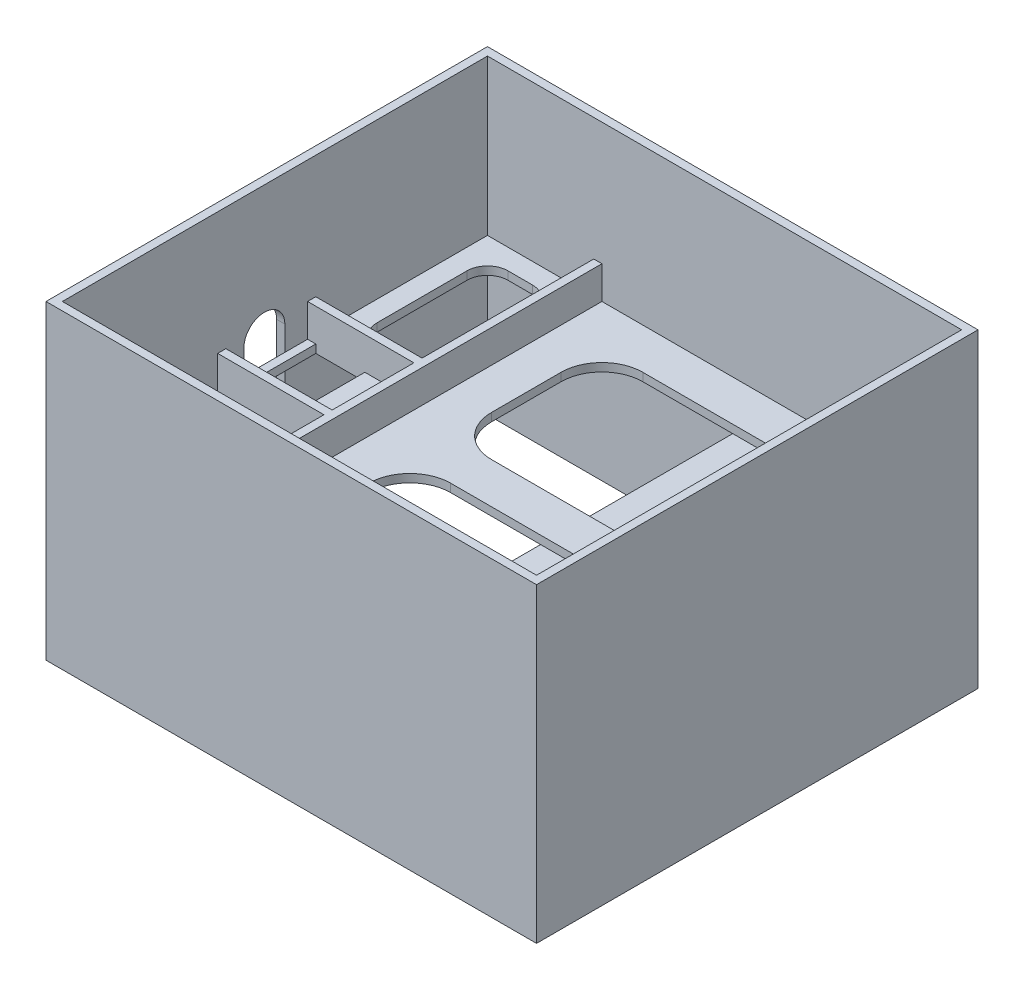
SolidWorks part; units mm, degrees
ref_plane "Front Plane" through (0, 0, 0) normal (0, 0, 1) x (1, 0, 0)
ref_plane "Top Plane" through (0, 0, 0) normal (0, 1, 0) x (1, 0, 0)
ref_plane "Right Plane" through (0, 0, 0) normal (1, 0, 0) x (0, 0, -1)
sketch "Sketch1" plane through (0, 0, 0) normal (0, 1, 0) x (1, 0, 0)
  line L1 (-113.8745, -60.9464) -> (-53.8745, -60.9464)
  line L2 (-113.8745, -60.9464) -> (-113.8745, -6.9464)
  line L3 (-113.8745, -6.9464) -> (-53.8745, -6.9464)
  line L4 (-53.8745, -60.9464) -> (-53.8745, -6.9464)
  dimension "D1" = 60
  dimension "D2" = 54
extrude "Boss-Extrude1" add sketch "Sketch1" along normal blind 38
sketch "Sketch2" plane through (0, 38, 0) normal (0, 1, 0) x (1, 0, 0)
  line L0 (-53.8745, -60.9464) -> (-53.8745, -6.9464) construction
  line L1 (-54.8745, -7.9464) -> (-98.8745, -7.9464)
  line L2 (-54.8745, -7.9464) -> (-54.8745, -59.9464)
  line L3 (-54.8745, -59.9464) -> (-98.8745, -59.9464)
  line L4 (-98.8745, -7.9464) -> (-98.8745, -59.9464)
  line L5 (-53.8745, -6.9464) -> (-113.8745, -6.9464) construction
  line L6 (-113.8745, -60.9464) -> (-53.8745, -60.9464) construction
  dimension "D1" = 1
  dimension "D2" = 1
  dimension "D3" = 1
  dimension "D4" = 44
extrude "Cut-Extrude1" cut sketch "Sketch2" against normal blind 19
sketch "Sketch3" plane through (0, 0, 0) normal (0, -1, 0) x (-1, 0, 0)
  line L0 (113.8745, -60.9464) -> (53.8745, -60.9464) construction
  line L1 (112.8745, -59.9464) -> (77.8745, -59.9464)
  line L2 (112.8745, -59.9464) -> (112.8745, -7.9464)
  line L3 (112.8745, -7.9464) -> (77.8745, -7.9464)
  line L4 (77.8745, -59.9464) -> (77.8745, -7.9464)
  line L5 (113.8745, -6.9464) -> (113.8745, -60.9464) construction
  line L6 (53.8745, -6.9464) -> (113.8745, -6.9464) construction
  dimension "D1" = 1
  dimension "D2" = 35
  dimension "D3" = 1
  dimension "D4" = 1
extrude "Cut-Extrude2" cut sketch "Sketch3" against normal blind 18
sketch "Sketch4" plane through (0, 18, 0) normal (0, -1, 0) x (-1, 0, 0)
  line L0 (77.8745, -59.9464) -> (112.8745, -59.9464) construction
  line L1 (111.8745, -39.9464) -> (105.8745, -39.9464)
  line L2 (111.8745, -39.9464) -> (111.8745, -29.9464)
  line L3 (111.8745, -29.9464) -> (105.8745, -29.9464)
  line L4 (105.8745, -39.9464) -> (105.8745, -29.9464)
  line L5 (112.8745, -7.9464) -> (77.8745, -7.9464) construction
  line L6 (112.8745, -59.9464) -> (112.8745, -7.9464) construction
  dimension "D1" = 20
  dimension "D2" = 22
  dimension "D3" = 1
  dimension "D4" = 6
extrude "Cut-Extrude3" cut sketch "Sketch4" against normal blind 38
sketch "Sketch5" plane through (0, 38, 0) normal (0, 1, 0) x (1, 0, 0)
  line L0 (-53.8745, -6.9464) -> (-113.8745, -6.9464) construction
  line L1 (-98.8745, -59.9464) -> (-112.8745, -59.9464)
  line L2 (-98.8745, -59.9464) -> (-98.8745, -7.9464)
  line L3 (-98.8745, -7.9464) -> (-112.8745, -7.9464)
  line L4 (-112.8745, -59.9464) -> (-112.8745, -7.9464)
  line L5 (-113.8745, -6.9464) -> (-113.8745, -60.9464) construction
  dimension "D1" = 1
  dimension "D2" = 1
extrude "Cut-Extrude5" cut sketch "Sketch5" against normal blind 15
sketch "Sketch6" plane through (0, 23, 0) normal (0, 1, 0) x (1, 0, 0)
  line L0 (-112.8745, -59.9464) -> (-98.8745, -59.9464) construction
  line L1 (-112.8745, -7.9464) -> (-99.8745, -7.9464)
  line L2 (-112.8745, -7.9464) -> (-112.8745, -59.9464)
  line L3 (-112.8745, -59.9464) -> (-99.8745, -59.9464)
  line L4 (-99.8745, -7.9464) -> (-99.8745, -59.9464)
  line L5 (-98.8745, -59.9464) -> (-98.8745, -7.9464) construction
  dimension "D1" = 1
extrude "Cut-Extrude6" cut sketch "Sketch6" against normal blind 4
sketch "Sketch8" plane through (0, 0, 0) normal (0, -1, 0) x (-1, 0, 0)
  line L0 (53.8745, -60.9464) -> (53.8745, -6.9464) construction
  line L1 (73.3745, -11.4464) -> (58.3745, -11.4464)
  line L2 (73.3745, -11.4464) -> (73.3745, -24.4464)
  line L3 (73.3745, -24.4464) -> (58.3745, -24.4464)
  line L4 (58.3745, -11.4464) -> (58.3745, -24.4464)
  line L6 (53.8745, -6.9464) -> (113.8745, -6.9464) construction
  dimension "D1" = 15
  dimension "D2" = 13
  dimension "D3" = 4.5
  dimension "D4" = 4.5
extrude "Cut-Extrude7" cut sketch "Sketch8" against normal blind 6
sketch "Sketch10" plane through (-73.3745, 0, 0) normal (1, 0, 0) x (0, 0, -1)
  line L0 (-11.4464, 6) -> (-11.4464, 0) construction
  line L1 (-24.4464, 6) -> (-11.4464, 6)
  line L2 (-24.4464, 6) -> (-24.4464, 1)
  line L3 (-24.4464, 1) -> (-11.4464, 1)
  line L4 (-11.4464, 6) -> (-11.4464, 1)
  line L5 (-24.4464, 0) -> (-11.4464, 0) construction
  point P7 (-11.9162, 2.727)
  dimension "D1" = 1
extrude "Cut-Extrude8" cut sketch "Sketch10" against normal blind 6
sketch "Sketch11" plane through (0, 0, 0) normal (0, -1, 0) x (1, 0, 0)
  line L0 (-113.8745, 60.9464) -> (-53.8745, 60.9464) construction
  line L1 (-67.8745, 50.9464) -> (-63.8745, 50.9464)
  line L2 (-67.8745, 50.9464) -> (-67.8745, 45.9464)
  line L3 (-67.8745, 45.9464) -> (-63.8745, 45.9464)
  line L4 (-63.8745, 50.9464) -> (-63.8745, 45.9464)
  line L5 (-53.8745, 60.9464) -> (-53.8745, 6.9464) construction
  dimension "D1" = 4
  dimension "D2" = 5
  dimension "D3" = 10
  dimension "D4" = 10
extrude "Cut-Extrude9" cut sketch "Sketch11" against normal blind 3
sketch "Sketch12" plane through (-67.8745, 0, 0) normal (1, 0, 0) x (0, 0, -1)
  line L0 (-50.9464, 3) -> (-50.9464, 0) construction
  line L1 (-45.9464, 3) -> (-50.9464, 3)
  line L2 (-45.9464, 3) -> (-45.9464, 1)
  line L3 (-45.9464, 1) -> (-50.9464, 1)
  line L4 (-50.9464, 3) -> (-50.9464, 1)
  line L5 (-50.9464, 0) -> (-45.9464, 0) construction
  point P7 (-49.533, -3.8829)
  dimension "D1" = 1
extrude "Cut-Extrude10" cut sketch "Sketch12" against normal blind 13
sketch "Sketch13" plane through (-113.8745, 0, 0) normal (-1, 0, 0) x (0, 0, 1)
  line L0 (35.233, 15) -> (35.233, 22) construction
  line L1 (32.733, 15) -> (32.733, 22)
  line L2 (37.733, 15) -> (37.733, 22)
  line L3 (59.9464, 18) -> (7.9464, 18) construction
  line L4 (39.9464, 19) -> (29.9464, 19) construction
  arc A0 (32.733, 15) -> (37.733, 15) centre (35.233, 15) ccw
  arc A1 (37.733, 22) -> (32.733, 22) centre (35.233, 22) ccw
  point P2 (35.233, 18.5)
  point P7 (0, 0)
  point P8 (14.7226, 4.5519)
  dimension "D1" = 3
  dimension "D2" = 3
  dimension "D3" = 2.5
extrude "Cut-Extrude11" cut sketch "Sketch13" against normal blind 1
sketch "Sketch14" plane through (0, 19, 0) normal (0, 1, 0) x (1, 0, 0)
  line L0 (-99.8745, -59.9464) -> (-99.8745, -7.9464) construction
  line L1 (-112.8745, -40.9464) -> (-99.8745, -40.9464)
  line L2 (-112.8745, -40.9464) -> (-112.8745, -39.9464)
  line L3 (-112.8745, -39.9464) -> (-99.8745, -39.9464)
  line L4 (-99.8745, -40.9464) -> (-99.8745, -39.9464)
  line L5 (-112.8745, -37.733) -> (-112.8745, -59.9464) construction
  line L6 (-105.8745, -39.9464) -> (-111.8745, -39.9464) construction
  point P6 (-120.1002, -35.2386)
  point P7 (-123.1182, -45.5085)
  point P8 (-107.1478, -38.8588)
  dimension "D1" = 0
  dimension "D2" = 1
  dimension "D3" = 0
extrude "Boss-Extrude2" add sketch "Sketch14" along normal blind 4
sketch "Sketch15" plane through (0, 19, 0) normal (0, 1, 0) x (1, 0, 0)
  line L0 (-112.8745, -7.9464) -> (-112.8745, -32.733) construction
  line L1 (-112.8745, -29.9464) -> (-99.8745, -29.9464)
  line L2 (-112.8745, -29.9464) -> (-112.8745, -28.9464)
  line L3 (-112.8745, -28.9464) -> (-99.8745, -28.9464)
  line L4 (-99.8745, -29.9464) -> (-99.8745, -28.9464)
  line L5 (-99.8745, -39.9464) -> (-99.8745, -7.9464) construction
  line L6 (-111.8745, -29.9464) -> (-105.8745, -29.9464) construction
  point P8 (-103.7086, -29.8744)
  dimension "D1" = 0
  dimension "D2" = 1
extrude "Boss-Extrude3" add sketch "Sketch15" along normal blind 4
sketch "Sketch16" plane through (0, 19, 0) normal (0, 1, 0) x (1, 0, 0)
  line L0 (-98.8745, -59.9464) -> (-54.8745, -59.9464) construction
  line L1 (-64.8745, -54.9464) -> (-88.8745, -54.9464)
  line L2 (-59.8745, -49.9464) -> (-59.8745, -41.4464)
  line L3 (-64.8745, -36.4464) -> (-88.8745, -36.4464)
  line L4 (-93.8745, -49.9464) -> (-93.8745, -41.4464)
  line L5 (-88.8745, -31.4464) -> (-64.8745, -31.4464)
  line L6 (-93.8745, -26.4464) -> (-93.8745, -17.9464)
  line L7 (-88.8745, -12.9464) -> (-64.8745, -12.9464)
  line L8 (-59.8745, -26.4464) -> (-59.8745, -17.9464)
  line L9 (-54.8745, -59.9464) -> (-54.8745, -7.9464) construction
  line L10 (-98.8745, -7.9464) -> (-98.8745, -59.9464) construction
  line L11 (-54.8745, -7.9464) -> (-98.8745, -7.9464) construction
  arc A0 (-64.8745, -31.4464) -> (-59.8745, -26.4464) centre (-64.8745, -26.4464) ccw
  arc A1 (-64.8745, -12.9464) -> (-59.8745, -17.9464) centre (-64.8745, -17.9464) cw
  arc A2 (-93.8745, -17.9464) -> (-88.8745, -12.9464) centre (-88.8745, -17.9464) cw
  arc A3 (-88.8745, -31.4464) -> (-93.8745, -26.4464) centre (-88.8745, -26.4464) cw
  arc A4 (-88.8745, -54.9464) -> (-93.8745, -49.9464) centre (-88.8745, -49.9464) cw
  arc A5 (-88.8745, -36.4464) -> (-93.8745, -41.4464) centre (-88.8745, -41.4464) ccw
  arc A6 (-59.8745, -41.4464) -> (-64.8745, -36.4464) centre (-64.8745, -41.4464) ccw
  arc A7 (-64.8745, -54.9464) -> (-59.8745, -49.9464) centre (-64.8745, -49.9464) ccw
  point P22 (-93.8745, -12.9464)
  point P25 (-93.8745, -31.4464)
  dimension "D9" = 5
  dimension "D1" = 5
  dimension "D2" = 5
  dimension "D3" = 5
  dimension "D4" = 5
  dimension "D5" = 5
  dimension "D6" = 5
  dimension "D7" = 5
  dimension "D8" = 18.5
extrude "Cut-Extrude12" cut sketch "Sketch16" against normal blind 1
sketch "Sketch17" plane through (0, 19, 0) normal (0, 1, 0) x (1, 0, 0)
  line L0 (-112.8745, -40.9464) -> (-112.8745, -59.9464) construction
  line L1 (-104.8745, -57.4464) -> (-107.8745, -57.4464)
  line L2 (-102.3745, -54.9464) -> (-102.3745, -45.9464)
  line L3 (-104.8745, -43.4464) -> (-107.8745, -43.4464)
  line L4 (-110.3745, -54.9464) -> (-110.3745, -45.9464)
  line L5 (-104.8745, -26.4464) -> (-107.8745, -26.4464)
  line L6 (-102.3745, -23.9464) -> (-102.3745, -12.9464)
  line L7 (-104.8745, -10.4464) -> (-107.8745, -10.4464)
  line L8 (-110.3745, -23.9464) -> (-110.3745, -12.9464)
  line L9 (-99.8745, -59.9464) -> (-99.8745, -40.9464) construction
  line L10 (-112.8745, -40.9464) -> (-99.8745, -40.9464) construction
  line L11 (-112.8745, -59.9464) -> (-99.8745, -59.9464) construction
  line L12 (-99.8745, -28.9464) -> (-112.8745, -28.9464) construction
  line L13 (-112.8745, -7.9464) -> (-112.8745, -28.9464) construction
  line L14 (-99.8745, -28.9464) -> (-99.8745, -7.9464) construction
  line L15 (-99.8745, -7.9464) -> (-112.8745, -7.9464) construction
  arc A0 (-102.3745, -12.9464) -> (-104.8745, -10.4464) centre (-104.8745, -12.9464) ccw
  arc A1 (-107.8745, -10.4464) -> (-110.3745, -12.9464) centre (-107.8745, -12.9464) ccw
  arc A2 (-107.8745, -26.4464) -> (-110.3745, -23.9464) centre (-107.8745, -23.9464) cw
  arc A3 (-104.8745, -26.4464) -> (-102.3745, -23.9464) centre (-104.8745, -23.9464) ccw
  arc A4 (-102.3745, -45.9464) -> (-104.8745, -43.4464) centre (-104.8745, -45.9464) ccw
  arc A5 (-107.8745, -43.4464) -> (-110.3745, -45.9464) centre (-107.8745, -45.9464) ccw
  arc A6 (-107.8745, -57.4464) -> (-110.3745, -54.9464) centre (-107.8745, -54.9464) cw
  arc A7 (-104.8745, -57.4464) -> (-102.3745, -54.9464) centre (-104.8745, -54.9464) ccw
  point P4 (-112.3884, -13.4853)
  dimension "D9" = 2.5
  dimension "D1" = 2.5
  dimension "D2" = 2.5
  dimension "D3" = 2.5
  dimension "D4" = 2.5
  dimension "D5" = 2.5
  dimension "D6" = 2.5
  dimension "D7" = 2.5
  dimension "D8" = 2.5
extrude "Cut-Extrude13" cut sketch "Sketch17" against normal blind 1
